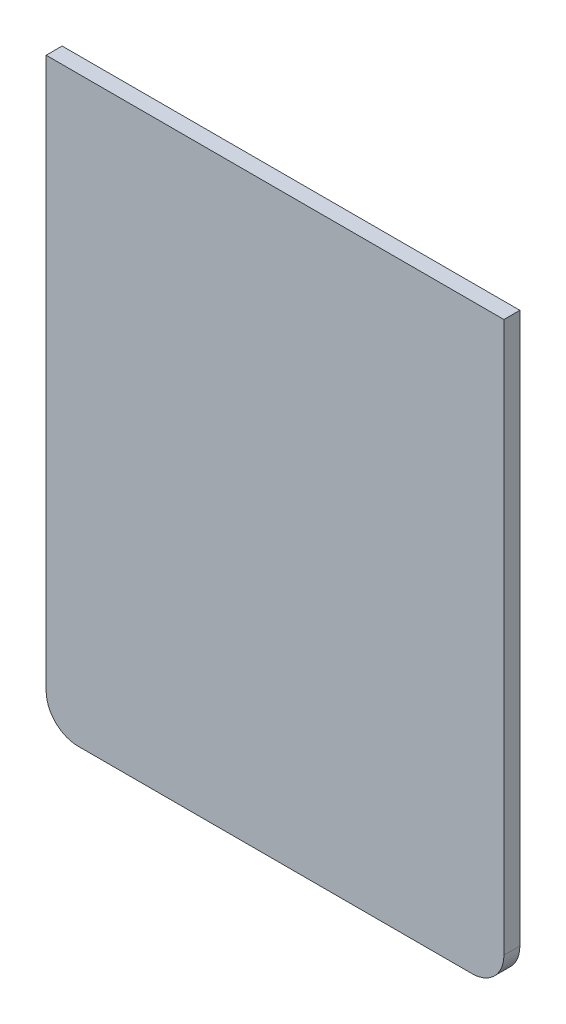
SolidWorks part; units mm, degrees
material "Beech"
ref_plane "Front Plane" through (0, 0, 0) normal (0, 0, 1) x (1, 0, 0)
ref_plane "Top Plane" through (0, 0, 0) normal (0, 1, 0) x (1, 0, 0)
ref_plane "Right Plane" through (0, 0, 0) normal (1, 0, 0) x (0, 0, -1)
sketch "Sketch1" plane through (0, 0, 0) normal (0, 0, 1) x (1, 0, 0)
  line L2 (-19.05, 903.0272) -> (163.1, 903.0272)
  line L6 (-6.35, 671.2522) -> (150.4, 671.2522)
  line L7 (163.1, 683.9522) -> (163.1, 903.0272)
  line L10 (-19.05, 903.0272) -> (-19.05, 683.9522)
  arc A2 (-19.05, 683.9522) -> (-6.35, 671.2522) centre (-6.35, 683.9522) ccw
  arc A3 (150.4, 671.2522) -> (163.1, 683.9522) centre (150.4, 683.9522) ccw
extrude "Boss-Extrude1" add sketch "Sketch1" along normal blind 6.35
hole_wizard "Hole1" positions "Sketch2" profile "Sketch3" legacy
sketch "Sketch2" plane through (72.025, -454.7856, -38.1) normal (0, 0, 1) x (1, 0, 0)
  point P0 (-78.375, 1310.1878)
  point P3 (-78.375, 1138.7378)
  point P6 (78.375, 1138.7378)
  point P9 (78.375, 1310.1878)
sketch "Sketch3" plane through (-6.35, 855.4022, -38.1) normal (1, 0, 0) x (0, -1, 0)
  line L0 (0, 0) -> (0, 32.7039)
  line L1 (0, 32.7039) -> (1.5875, 31.75)
  line L2 (1.5875, 31.75) -> (1.5875, 4.0177)
  line L3 (1.5875, 4.0177) -> (5.08, 0)
  line L4 (5.08, 0) -> (0, 0)
  line L5 (0, -14.3089) -> (0, 102.4216) construction
  line L6 (0, 32.7039) -> (-1.5875, 31.75) construction
  line L7 (-1.5875, 4.0177) -> (-5.08, 0) construction
  dimension "Diameter" = 3.175
  dimension "Depth" = 31.75
  dimension "C-Sink Diameter" = 10.16
  dimension "C-Sink Angle" = 82
  dimension "Drill Angle" = 118
